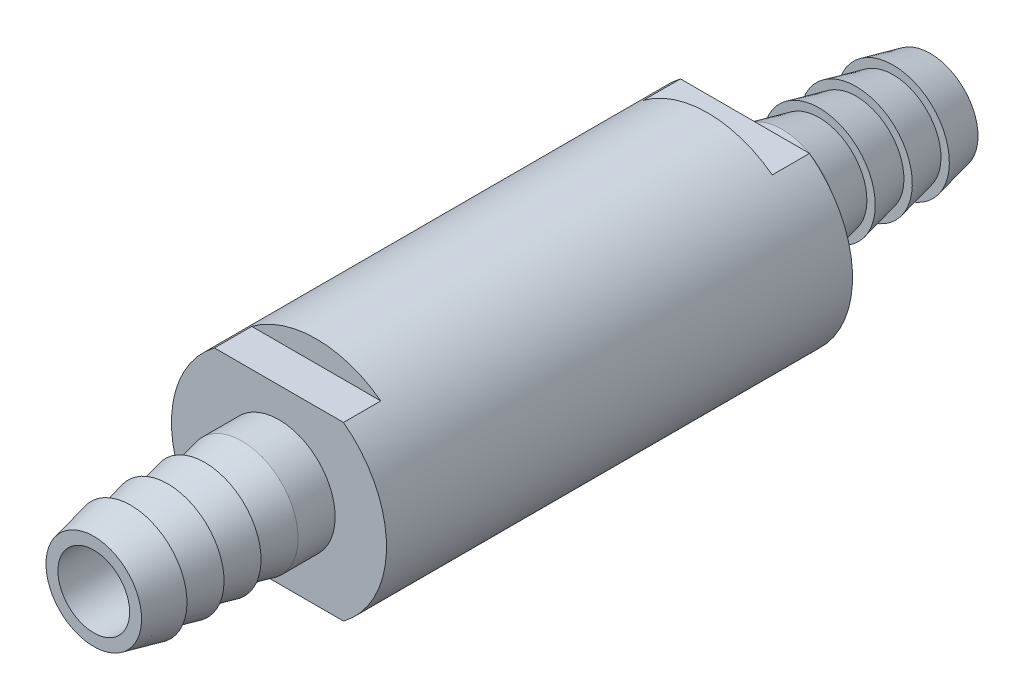
SolidWorks part; units mm, degrees
ref_plane "Front Plane" through (0, 0, 0) normal (0, 0, 1) x (1, 0, 0)
ref_plane "Top Plane" through (0, 0, 0) normal (0, 1, 0) x (1, 0, 0)
ref_plane "Right Plane" through (0, 0, 0) normal (1, 0, 0) x (0, 0, -1)
sketch "Sketch1" plane through (0, 0, 0) normal (1, 0, 0) x (0, 0, -1)
  line L0 (30.9562, 0) -> (-30.9562, 0) construction
  line L1 (55.5625, 0) -> (-55.5625, 0) construction
  line L2 (-30.9562, -14.2875) -> (-30.9563, 14.2875) construction
  line L3 (-55.5625, -7.4613) -> (-55.5625, 7.4612) construction
  line L4 (-50.6412, -6.35) -> (-50.6412, 6.35) construction
  line L5 (30.9563, -14.2875) -> (30.9562, 14.2875) construction
  line L6 (-55.5625, -4.7625) -> (-55.5625, 4.7625) construction
  point P3 (0, 0)
  point P6 (0, 0)
  point P9 (-30.9562, 0)
  point P11 (-55.5625, 0)
  point P15 (-50.6412, 0)
  point P17 (30.9562, 0)
  point P20 (-55.5625, 0)
sketch "Sketch2" plane through (0, 0, 0) normal (1, 0, 0) x (0, 0, -1)
  line L0 (-55.5625, 0) -> (-55.5625, 7.4612)
  line L1 (-55.5625, -7.4613) -> (-55.5625, 7.4612) construction
  line L2 (-55.5625, 7.4612) -> (-30.9562, 7.4612)
  line L3 (-30.9562, -14.2875) -> (-30.9563, 14.2875) construction
  line L4 (-30.9562, 7.4612) -> (-30.9563, 14.2875)
  line L5 (-30.9563, 14.2875) -> (30.9563, 14.2875)
  line L6 (30.9563, 14.2875) -> (30.9563, 7.4612)
  line L7 (30.9563, -14.2875) -> (30.9562, 14.2875) construction
  line L8 (30.9563, 7.4612) -> (55.5625, 7.4612)
  line L9 (55.5625, 7.4612) -> (55.5625, 0)
  line L10 (55.5625, 0) -> (-55.5625, 0)
revolve "Revolve1" add sketch "Sketch2" angle 360 about L0
sketch "Sketch3" plane through (0, 0, -30.9563) normal (0, 0, -1) x (-1, 0, 0)
  line L0 (-8.5725, 11.43) -> (8.5725, 11.43)
  circle A0 centre (0, 0) radius 14.2875 construction
  arc A1 (8.5725, 11.43) -> (-8.5725, 11.43) centre (0, 0) ccw
  dimension "D1" = 11.43
extrude "Cut-Extrude1" cut sketch "Sketch3" against normal blind 4.953
mirror "Mirror1" about plane through (0, 0, 0) normal (0, 1, 0) of "Cut-Extrude1"
mirror "Mirror2" about plane through (0, 0, 0) normal (0, 0, 1) of "Mirror1", "Cut-Extrude1"
sketch "Sketch4" plane through (0, 0, 0) normal (1, 0, 0) x (0, 0, -1)
  line L2 (-55.5625, 7.4612) -> (-55.5625, 6.35)
  line L9 (-55.5625, -7.4613) -> (-55.5625, 7.4612) construction
  line L10 (-55.5625, 6.35) -> (-50.6412, 7.4612)
  line L11 (-30.9562, 7.4612) -> (-55.5625, 7.4612) construction
  line L12 (-50.6412, 7.4612) -> (-55.5625, 7.4612)
  dimension "D1" = 1.1113
  dimension "D2" = 4.9213
revolve "Cut-Revolve1" cut sketch "Sketch4" angle 360 about L1
pattern_linear "LPattern1" count 4 spacing 4.9213 along (0, 0, -1) of "Cut-Revolve1"
mirror "Mirror3" about plane through (0, 0, 0) normal (0, 0, 1) of "LPattern1", "Cut-Revolve1"
sketch "Sketch5" plane through (0, 0, 55.5625) normal (0, 0, 1) x (1, 0, 0)
  line L0 (0, -4.7625) -> (0, 4.7625) construction
  circle A0 centre (0, 0) radius 4.7625
  dimension "D1" = 9.525
extrude "Cut-Extrude2" cut sketch "Sketch5" against normal up to vertex (24.6062 mm away) up to point (0, 0, 30.9562)
mirror "Mirror4" about plane through (0, 0, 0) normal (0, 0, 1) of "Cut-Extrude2"
sketch "Sketch6" plane through (0, 0, 30.9563) normal (0, 0, 1) x (1, 0, 0)
  line L0 (-14.2875, 0) -> (14.2875, 0) construction
  arc A2 (-8.5725, 11.43) -> (-8.5725, -11.43) centre (0, 0) ccw construction
  arc A3 (8.5725, -11.43) -> (8.5725, 11.43) centre (0, 0) ccw construction
equation "\"D1@Cut-Extrude1\"=\"Middle Length@Sketch1\"*.08"
equation "\"D3@LPattern1\"=\"Barb Length@Sketch1\""
equation "\"D1@Sketch5\"=\"Inlet/Outlet ID@Sketch1\""
equation "\"Inlet/Outlet Large OD@Sketch1\"=\"For Hose ID@Sketch1\"*1.175"
equation "\"Barb Length@Sketch1\"=((\"Length@Sketch1\"-\"Middle Length@Sketch1\")/2)*.2"
equation "\"D1@Sketch4\"=(\"Inlet/Outlet Large OD@Sketch1\"-\"For Hose ID@Sketch1\")/2"
equation "\"D2@Sketch4\"=\"Barb Length@Sketch1\""
equation "\"Inlet/Outlet ID@Sketch1\"  = \"Inlet/Outlet Small OD@Sketch1\"*.75"
equation "\"D1@Sketch3\"=\"Middle OD@Sketch1\"*.4"
